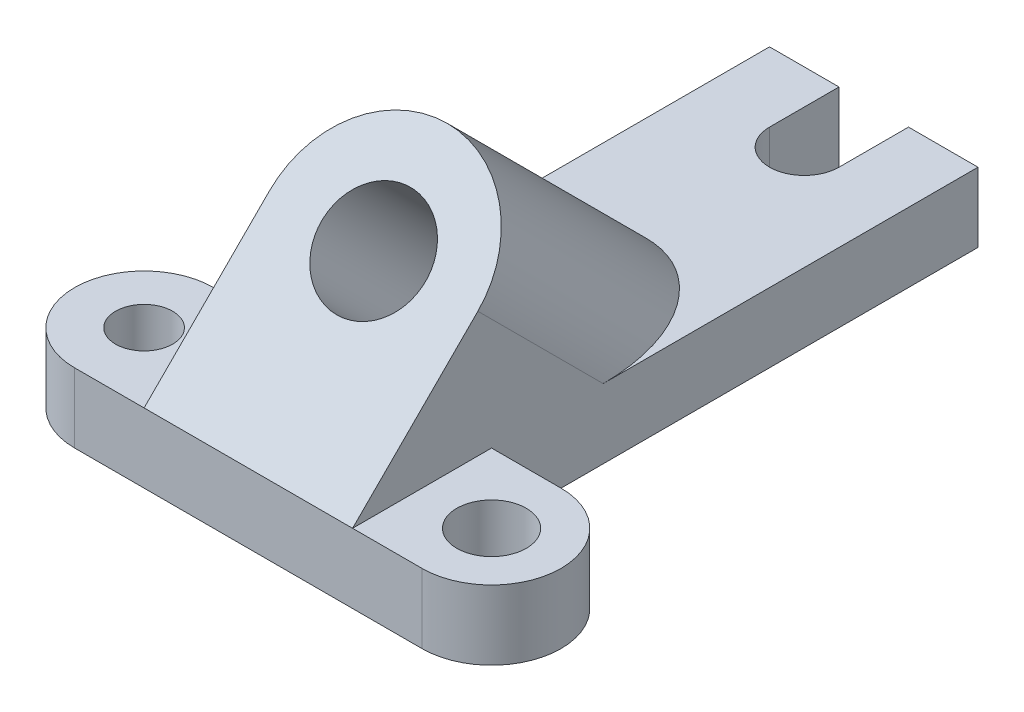
SolidWorks part; units mm, degrees
ref_plane "Front Plane" through (0, 0, 0) normal (0, 0, 1) x (1, 0, 0)
ref_plane "Top Plane" through (0, 0, 0) normal (0, 1, 0) x (1, 0, 0)
ref_plane "Right Plane" through (0, 0, 0) normal (1, 0, 0) x (0, 0, -1)
sketch "Sketch1" plane through (0, 0, 0) normal (0, 1, 0) x (1, 0, 0)
  line L0 (30, -43.4931) -> (30, 96.5069)
  line L3 (30, 96.5069) -> (-30, 96.5069)
  line L5 (30, -96.5069) -> (-30, 96.5069) construction
  line L6 (30, 96.5069) -> (-30, -96.5069) construction
  line L7 (-50, -43.4931) -> (-30, -43.4931)
  line L9 (-50, -83.4931) -> (50, -83.4931)
  line L11 (-30, -43.4931) -> (-30, 96.5069)
  line L12 (30, -43.4931) -> (50, -43.4931)
  circle A0 centre (-50, -63.4931) radius 20
  circle A1 centre (50, -63.4931) radius 20
  circle A2 centre (50, -63.4931) radius 10
  circle A3 centre (-50, -63.4931) radius 8.2173
  point P0 (0, 0)
  point P16 (0, 0)
  dimension "D3" = 40
  dimension "D4" = 20
  dimension "D1" = 100
  dimension "D5" = 180
  dimension "D6" = 60
extrude "Boss-Extrude1" add sketch "Sketch1" against normal blind 20 contours A0 A3 | A1 A2 | A2 | A1 L12 L0 L3 L11 L7 A0 L9
sketch "Sketch2" plane through (0, 0, 0) normal (0, 1, 0) x (1, 0, 0)
  line L0 (30, 96.5069) -> (-30, 96.5069) construction
  line L1 (-10, 96.5069) -> (10, 96.5069)
  line L2 (-10, 96.5069) -> (-10, 76.5069)
  line L4 (10, 96.5069) -> (10, 76.5069)
  arc A0 (-10, 76.5069) -> (10, 76.5069) centre (0, 76.5069) ccw
  dimension "D1" = 20
  dimension "D2" = 20
  dimension "D3" = 20
extrude "Cut-Extrude1" cut sketch "Sketch2" against normal blind 20
sketch "Sketch4" plane through (30, 0, 0) normal (1, 0, 0) x (0, 0, -1)
  line L0 (-83.4931, 0) -> (-26.2174, 57.2756) construction
  line L1 (-43.4931, 0) -> (-83.4931, 0) construction
  dimension "D1" = 45
  dimension "D2" = 81
ref_plane "Plane1" through (0, 41.7465, 41.7465) normal (0, 0.7071, 0.7071) x (1, 0, 0)
sketch "Sketch5" plane through (0, 41.7465, 41.7465) normal (0, 0.7071, 0.7071) x (1, 0, 0)
  line L0 (-50, -59.0385) -> (50, -59.0385) construction
  line L1 (-30, -59.0385) -> (30, -59.0385)
  line L2 (-30, -59.0385) -> (-30, -8.0385)
  line L3 (-30, -8.0385) -> (30, -8.0385)
  line L4 (30, -59.0385) -> (30, -8.0385)
  line L5 (30, -59.0385) -> (30, 21.9615) construction
  circle A0 centre (0, -8.0385) radius 30
  circle A1 centre (0, -8.0385) radius 15
  dimension "D2" = 60
  dimension "D3" = 30
  dimension "D1" = 51
extrude "Boss-Extrude2" add sketch "Sketch5" against normal up to next contours A0 L2 L1 L4 | A1 L3 A0 | A1 L3 A0
